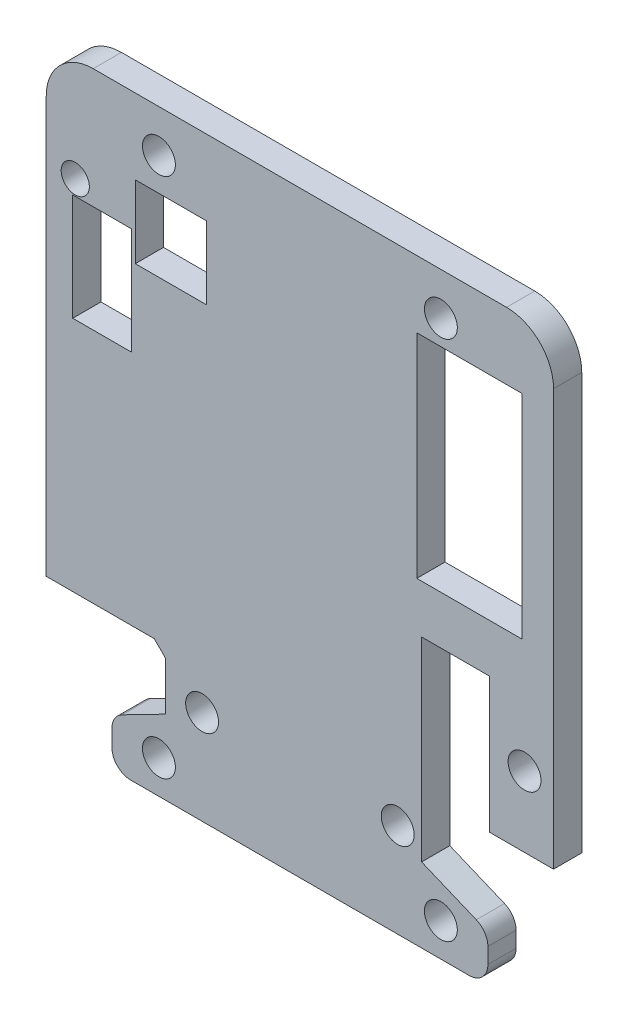
SolidWorks part; units mm, degrees
ref_plane "Front Plane" through (0, 0, 0) normal (0, 0, 1) x (1, 0, 0)
ref_plane "Top Plane" through (0, 0, 0) normal (0, 1, 0) x (1, 0, 0)
ref_plane "Right Plane" through (0, 0, 0) normal (1, 0, 0) x (0, 0, -1)
sketch "Sketch2" plane through (0, 0, 0) normal (0, 0, -1) x (-1, 0, 0)
  line L0 (-11.4411, 47.9161) -> (-14.8198, 47.9161)
  line L2 (-11.4411, 47.9161) -> (-11.4411, 26.1643)
  line L3 (-11.4411, 26.1643) -> (-0.269, 26.1643)
  line L4 (-0.269, 47.9161) -> (-0.269, 26.1643)
  line L6 (30.0778, 43.1934) -> (36.3374, 43.1934)
  line L7 (30.0778, 43.1934) -> (30.0778, 31.8296)
  line L8 (30.0778, 31.8296) -> (36.3374, 31.8296)
  line L9 (36.3374, 43.1934) -> (36.3374, 31.8296)
  line L10 (-14.8198, 47.9161) -> (-14.8198, 6.6411)
  line L11 (-14.8198, 6.6411) -> (-3.3322, 6.6411)
  line L12 (-3.3322, 6.6411) -> (-2.1198, 5.4288)
  line L13 (-2.1198, 5.4288) -> (-2.1198, 0.2911)
  line L14 (-2.1198, 0.2911) -> (26.4552, 0.2911)
  line L15 (26.4552, 0.2911) -> (26.4552, 5.4288)
  line L16 (26.4552, 5.4288) -> (27.6675, 6.6411)
  line L17 (27.6675, 6.6411) -> (39.1552, 6.6411)
  line L18 (39.1552, 6.6411) -> (39.1552, 47.9161)
  line L19 (39.1552, 47.9161) -> (-14.8198, 47.9161)
  line L20 (-14.8198, 47.9161) -> (-14.8198, 6.6411)
  line L21 (-14.8198, 6.6411) -> (-7.9956, 6.6411)
  line L24 (-0.7808, 0.2911) -> (26.4552, 0.2911)
  line L25 (26.4552, 0.2911) -> (26.4552, 5.4288)
  line L26 (26.4552, 5.4288) -> (27.6675, 6.6411)
  line L27 (27.6675, 6.6411) -> (39.1552, 6.6411)
  line L28 (39.1552, 6.6411) -> (39.1552, 47.9161)
  line L29 (39.1552, 47.9161) -> (29.6796, 47.9161)
  line L31 (-7.9956, 6.6411) -> (-7.9956, 21.0223)
  line L32 (-7.9956, 21.0223) -> (-0.7808, 21.0223)
  line L33 (-0.7808, 0.2911) -> (-0.7808, 21.0223)
  line L34 (22.1203, 47.9161) -> (-0.269, 47.9161)
  line L36 (29.6796, 47.9161) -> (29.6796, 40.1856)
  line L37 (29.6796, 40.1856) -> (22.1203, 40.1856)
  line L38 (22.1203, 47.9161) -> (22.1203, 40.1856)
  line L39 (1.7614, 3.3786) -> (1.7614, 2.3786) construction
  line L40 (1.7614, 2.3786) -> (22.5739, 2.3786) construction
  line L41 (22.5739, 2.3786) -> (22.5739, 3.3786) construction
  line L42 (-11.7323, 15.1411) -> (-11.7323, 14.1411) construction
  circle A0 centre (36.0677, 44.8286) radius 1.5 construction
  circle A4 centre (1.7614, 2.3786) radius 1.75
  circle A5 centre (36.0677, 44.8286) radius 1.5
  circle A9 centre (22.5739, 2.3786) radius 1.75
  circle A10 centre (-11.7323, 14.1411) radius 1.75
  point P34 (-0.7808, 0.2911)
  dimension "D3" = 3.5
  dimension "D2" = 1
  dimension "D1" = 0
extrude "Boss-Extrude1" add sketch "Sketch2" against normal blind 3
sketch "Sketch3" plane through (0, 0, 0) normal (0, 0, 1) x (1, 0, 0)
  line L0 (-39.1552, 47.9161) -> (0.269, 47.9161)
  line L1 (14.8198, 47.9161) -> (14.8198, 50.9161)
  line L2 (9.8198, 55.9161) -> (-34.1552, 55.9161)
  line L3 (-39.1552, 50.9161) -> (-39.1552, 47.9161)
  line L4 (-27.1677, 51.4161) -> (2.8323, 51.4161) construction
  line L5 (-12.1677, 51.4161) -> (-12.1677, 48.4161) construction
  line L11 (-26.4552, 0.2911) -> (-31.081, -2.0832)
  line L12 (-32.1677, -3.8625) -> (-32.1677, -5.641)
  line L13 (11.4411, 26.1643) -> (11.4411, 47.9161) construction
  line L15 (0.269, 47.9161) -> (0.269, 48.7979)
  line L16 (0.269, 48.7979) -> (11.4411, 48.7979)
  line L17 (11.4411, 47.9161) -> (11.4411, 48.7979)
  line L18 (11.4411, 47.9161) -> (14.8198, 47.9161)
  line L19 (-30.1677, -7.641) -> (5.8323, -7.641)
  line L20 (7.8323, -5.641) -> (7.8323, -3.9754)
  line L21 (6.6002, -2.1287) -> (0.7808, 0.2911)
  line L22 (0.7808, 0.2911) -> (-26.4552, 0.2911)
  line L23 (-32.1677, -2.641) -> (7.8323, -2.641) construction
  line L24 (-27.1677, -4.0839) -> (2.8323, -4.0839) construction
  line L25 (-12.1677, -4.0839) -> (-12.1677, 48.4161) construction
  line L26 (-12.1677, 51.4161) -> (-12.1677, 55.9161) construction
  arc A0 (14.8198, 50.9161) -> (9.8198, 55.9161) centre (9.8198, 50.9161) ccw
  arc A1 (-34.1552, 55.9161) -> (-39.1552, 50.9161) centre (-34.1552, 50.9161) ccw
  circle A2 centre (-27.1677, 51.4161) radius 1.75
  circle A3 centre (2.8323, 51.4161) radius 1.75
  arc A8 (-31.081, -2.0832) -> (-32.1677, -3.8625) centre (-30.1677, -3.8625) ccw
  arc A9 (7.8323, -3.9754) -> (6.6002, -2.1287) centre (5.8323, -3.9754) ccw
  arc A10 (5.8323, -7.641) -> (7.8323, -5.641) centre (5.8323, -5.641) ccw
  arc A11 (-32.1677, -5.641) -> (-30.1677, -7.641) centre (-30.1677, -5.641) ccw
  circle A12 centre (-27.1677, -4.0839) radius 1.75
  circle A13 centre (2.8323, -4.0839) radius 1.75
  point P10 (-39.1552, 55.9161)
  point P28 (-12.1677, -2.641)
  dimension "D2" = 5
  dimension "D4" = 3.5
  dimension "D8" = 2
  dimension "D10" = 40
  dimension "D1" = 8
  dimension "D3" = 30
  dimension "D5" = 3
  dimension "D6" = 55.5
  dimension "D7" = 30
  dimension "D9" = 5
extrude "Boss-Extrude2" add sketch "Sketch3" along normal blind 3
